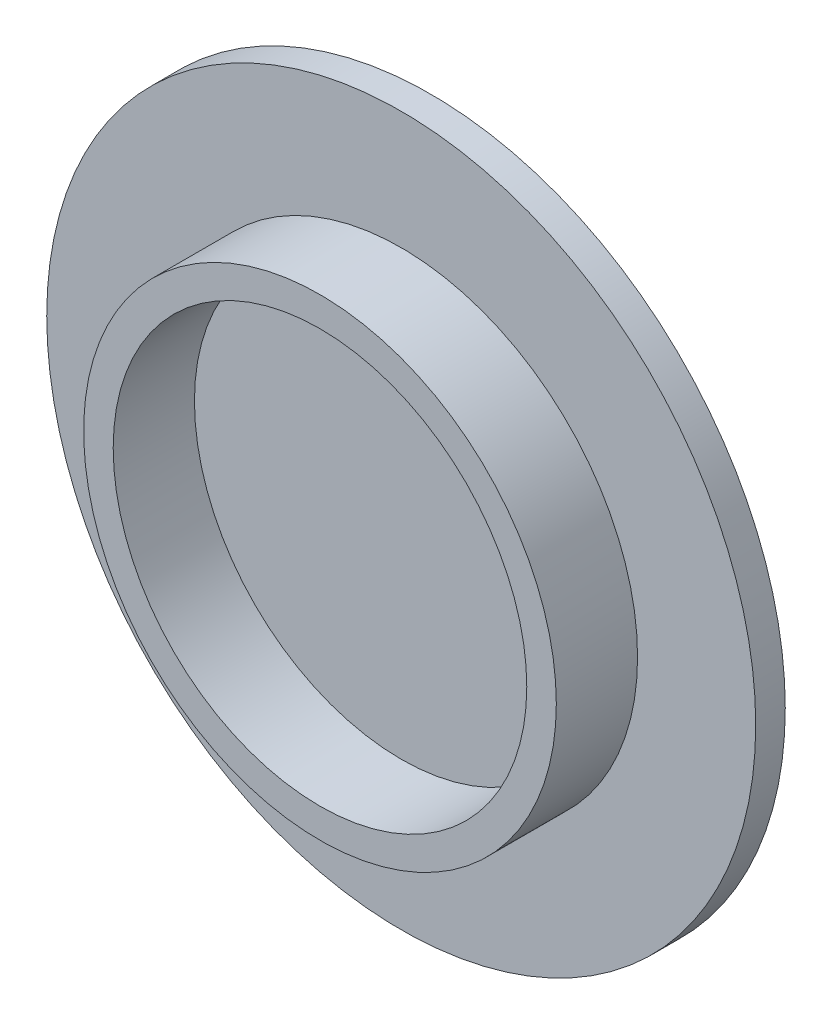
SolidWorks part; units mm, degrees
ref_plane "前视" through (0, 0, 0) normal (0, 0, 1) x (1, 0, 0)
ref_plane "上视" through (0, 0, 0) normal (0, 1, 0) x (1, 0, 0)
ref_plane "右视" through (0, 0, 0) normal (1, 0, 0) x (0, 0, -1)
sketch "草图1" plane through (0, 0, 0) normal (0, 0, 1) x (1, 0, 0)
  line L0 (0, 149.6675) -> (0, -153.1685) construction
  line L1 (-173.2992, 0) -> (179.7177, 0) construction
  circle A0 centre (0, 0) radius 120
  dimension "D1" = 240
extrude "拉伸1" add sketch "草图1" along normal blind 10
sketch "草图2" plane through (0, 0, 10) normal (0, 0, 1) x (1, 0, 0)
  circle A0 centre (0, 0) radius 80
  circle A1 centre (0, 0) radius 70
  dimension "D1" = 160
  dimension "D2" = 140
extrude "拉伸2" add sketch "草图2" along normal blind 27.5
